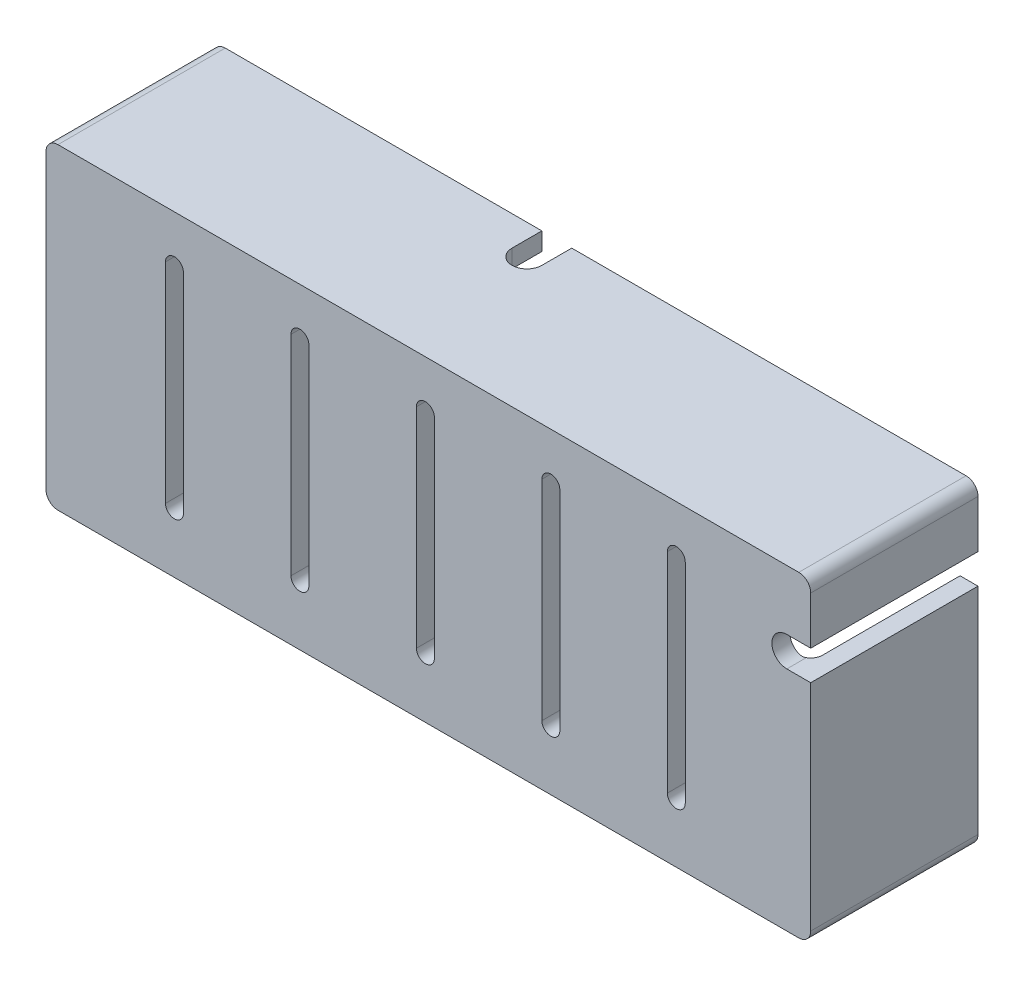
SolidWorks part; units mm, degrees
ref_plane "Plan de face" through (0, 0, 0) normal (0, 0, 1) x (1, 0, 0)
ref_plane "Plan de dessus" through (0, 0, 0) normal (0, 1, 0) x (1, 0, 0)
ref_plane "Plan de droite" through (0, 0, 0) normal (1, 0, 0) x (0, 0, -1)
sketch "Esquisse1" plane through (0, 0, 0) normal (0, 0, 1) x (1, 0, 0)
  line L0 (-61, 23.5) -> (61, -23.5) construction
  line L1 (-61, 23.5) -> (61, 23.5)
  line L2 (-61, 23.5) -> (-61, -23.5)
  line L3 (-61, -23.5) -> (61, -23.5)
  line L4 (61, 23.5) -> (61, -23.5)
  line L5 (-64, -26.5) -> (64, 26.5) construction
  line L6 (-64, 26.5) -> (64, 26.5)
  line L7 (-64, 26.5) -> (-64, -26.5)
  line L8 (-64, -26.5) -> (64, -26.5)
  line L9 (64, 26.5) -> (64, -26.5)
  dimension "D1" = 122
  dimension "D2" = 47
  dimension "D3" = 3
  dimension "D4" = 3
extrude "Boss.-Extru.1" add sketch "Esquisse1" along normal blind 25
sketch "Esquisse2" plane through (0, 0, 25) normal (0, 0, 1) x (1, 0, 0)
  line L1 (-64, 26.5) -> (64, 26.5)
  line L2 (-64, 26.5) -> (-64, -26.5)
  line L3 (-64, -26.5) -> (64, -26.5)
  line L4 (64, 26.5) -> (64, -26.5)
extrude "Boss.-Extru.2" add sketch "Esquisse2" along normal blind 3
sketch "Esquisse3" plane through (0, 0, 25) normal (0, 0, -1) x (-1, 0, 0)
  line L0 (-61, 18.5) -> (-56, 23.5)
  line L1 (-61, -23.5) -> (-61, 23.5) construction
  line L2 (-61, 23.5) -> (61, 23.5) construction
  line L3 (-56, 23.5) -> (-61, 23.5)
  line L4 (-61, 23.5) -> (-61, 18.5)
  line L5 (-61, 18.5) -> (-61.0063, 18.5)
  line L7 (-61, -23.5) -> (-61, -18.5)
  line L8 (-61, -18.5) -> (-56, -23.5)
  line L9 (61, -23.5) -> (-61, -23.5) construction
  line L10 (-56, -23.5) -> (-61, -23.5)
  line L11 (61, 23.5) -> (56, 23.5)
  line L12 (-61, 23.5) -> (61, 23.5) construction
  line L13 (56, 23.5) -> (61, 18.5)
  line L14 (61, 23.5) -> (61, -23.5) construction
  line L15 (61, 18.5) -> (61, 23.5)
  line L16 (61, -23.5) -> (61, -18.5)
  line L17 (61, 23.5) -> (61, -23.5) construction
  line L18 (61, -18.5) -> (56, -23.5)
  line L19 (61, -23.5) -> (-61, -23.5) construction
  line L20 (56, -23.5) -> (61, -23.5)
  line M1 (61, -23.5) -> (61, 23.5)
  line M2 (61, 23.5) -> (-61, 23.5)
  dimension "D1" = 5
  dimension "D2" = 5
  dimension "D3" = 5
  dimension "D4" = 5
  dimension "D5" = 5
  dimension "D6" = 5
  dimension "D7" = 5
  dimension "D8" = 5
extrude "Boss.-Extru.3" add sketch "Esquisse3" along normal blind 25 contours L13 M2 M1 | L16 L18 L20 | L7 L8 L10 | L0 L3 L4
sketch "Esquisse4" plane through (0, 0, 28) normal (0, 0, 1) x (1, 0, 0)
  line L1 (-64, 0) -> (64, 0) construction
  line L2 (-44, 18.5) -> (-44, -16.5)
  line L3 (-23, 18.5) -> (-23, -16.5)
  line L4 (-41, 18.5) -> (-41, -16.5)
  line L6 (-64, 26.5) -> (-64, -26.5) construction
  line L7 (-20, 18.5) -> (-20, -16.5)
  line L8 (-2, 18.5) -> (-2, -16.5)
  line L9 (1, 18.5) -> (1, -16.5)
  line L10 (19, 18.5) -> (19, -16.5)
  line L11 (22, 18.5) -> (22, -16.5)
  line L12 (40, 18.5) -> (40, -16.5)
  line L13 (43, 18.5) -> (43, -16.5)
  arc A0 (-44, 18.5) -> (-41, 18.5) centre (-42.5, 18.5) cw
  arc A1 (-44, -16.5) -> (-41, -16.5) centre (-42.5, -16.5) ccw
  arc A2 (-23, -16.5) -> (-20, -16.5) centre (-21.5, -16.5) ccw
  arc A3 (-23, 18.5) -> (-20, 18.5) centre (-21.5, 18.5) cw
  arc A4 (-2, -16.5) -> (1, -16.5) centre (-0.5, -16.5) ccw
  arc A5 (-2, 18.5) -> (1, 18.5) centre (-0.5, 18.5) cw
  arc A6 (19, -16.5) -> (22, -16.5) centre (20.5, -16.5) ccw
  arc A7 (19, 18.5) -> (22, 18.5) centre (20.5, 18.5) cw
  arc A8 (40, -16.5) -> (43, -16.5) centre (41.5, -16.5) ccw
  arc A9 (40, 18.5) -> (43, 18.5) centre (41.5, 18.5) cw
  dimension "D1" = 35
  dimension "D2" = 18.5
  dimension "D3" = 3
  dimension "D4" = 20
  dimension "D5" = 5
extrude "Enlèv. mat.-Extru.1" cut sketch "Esquisse4" against normal blind 3
sketch "Esquisse5" plane through (0, 0, 0) normal (0, 0, -1) x (-1, 0, 0)
  line L0 (56, 23.5) -> (61, 18.5) construction
  line L1 (-64, 26.5) -> (-55.783, 18.283) construction
  line L2 (-64, -26.5) -> (-55.3868, -17.8868) construction
  line L3 (-61, -18.5) -> (-56, -23.5) construction
  line L4 (64, -26.5) -> (56.4817, -18.9817) construction
  line L5 (61, -18.5) -> (56, -23.5) construction
  line L6 (61, -18.5) -> (56, -23.5) construction
  line L7 (64, 26.5) -> (55.3834, 17.8834) construction
  line L8 (56, 23.5) -> (61, 18.5) construction
  line L9 (-61, 18.5) -> (-56, 23.5) construction
  circle A0 centre (-60.6213, 23.1213) radius 1
  circle A1 centre (60.6213, 23.1213) radius 1
  circle A2 centre (-60.6213, -23.1213) radius 1
  circle A3 centre (60.6213, -23.1213) radius 1
  dimension "D1" = 2
  dimension "D2" = 2
  dimension "D3" = 2
  dimension "D4" = 2
  dimension "D5" = 3
  dimension "D6" = 3
  dimension "D7" = 3
  dimension "D8" = 3
extrude "Enlèv. mat.-Extru.2" cut sketch "Esquisse5" against normal blind 20
fillet "Congé1" radius 5 1 edges at (56, 23.5, 12.5)
fillet "Congé2" radius 5 7 edges at (-61, -18.5, 12.5) (-56, -23.5, 12.5) (-61, 18.5, 12.5) (-56, 23.5, 12.5) (56, -23.5, 12.5) (61, -18.5, 12.5) (61, 18.5, 12.5)
sketch "Esquisse6" plane through (64, 0, 0) normal (1, 0, 0) x (0, 0, -1)
  line L0 (-28, -26.5) -> (-28, 26.5) construction
  line L1 (-28, 16.5) -> (0, 16.5)
  line L2 (-28, 16.5) -> (-28, 11.5)
  line L3 (-28, 11.5) -> (0, 11.5)
  line L4 (0, 16.5) -> (0, 11.5)
  line L5 (0, -26.5) -> (0, 26.5) construction
  line L6 (-28, 26.5) -> (0, 26.5) construction
  dimension "D1" = 5
  dimension "D2" = 10
extrude "Enlèv. mat.-Extru.3" cut sketch "Esquisse6" against normal blind 3
sketch "Esquisse7" plane through (0, 26.5, 0) normal (0, 1, 0) x (1, 0, 0)
  line L0 (64, 0) -> (-64, 0) construction
  line L1 (-9, 0) -> (-4, 0)
  line L2 (-9, 0) -> (-9, -5)
  line L3 (-64, 0) -> (64, 0) construction
  line L4 (-4, 0) -> (-4, -5)
  line L5 (-64, -28) -> (-64, 0) construction
  arc A0 (-9, -5) -> (-4, -5) centre (-6.5, -5) ccw
  dimension "D4" = 2.5
  dimension "D1" = 5
  dimension "D2" = 5
  dimension "D3" = 55
extrude "Enlèv. mat.-Extru.4" cut sketch "Esquisse7" against normal blind 8
sketch "Esquisse9" plane through (0, -26.5, 0) normal (0, -1, 0) x (1, 0, 0)
  line L0 (-29, 0) -> (64, 0) construction
  line L1 (44, 0) -> (49, 0)
  line L2 (44, 0) -> (44, 5)
  line L4 (49, 0) -> (49, 5)
  line L5 (64, 28) -> (64, 0) construction
  arc A0 (44, 5) -> (49, 5) centre (46.5, 5) cw
  dimension "D3" = 2.5
  dimension "D1" = 5
  dimension "D2" = 15
  dimension "D4" = 5
extrude "Enlèv. mat.-Extru.6" cut sketch "Esquisse9" against normal blind 8
sketch "Esquisse10" plane through (0, 0, 28) normal (0, 0, 1) x (1, 0, 0)
  line L1 (61, 16.5) -> (60, 16.5)
  line L2 (61, 16.5) -> (61, 11.5)
  line L3 (61, 11.5) -> (60, 11.5)
  arc A0 (60, 16.5) -> (60, 11.5) centre (60, 14) ccw
  dimension "D1" = 2.5
  dimension "D2" = 1
  dimension "D3" = 5
extrude "Enlèv. mat.-Extru.7" cut sketch "Esquisse10" against normal blind 8
sketch "Esquisse13" plane through (-64, 0, 0) normal (-1, 0, 0) x (0, 0, 1)
  line L0 (0, 26.5) -> (0, -26.5) construction
  line L1 (0, 3) -> (2, 3)
  line L2 (0, 3) -> (0, -3)
  line L3 (0, -3) -> (2, -3)
  line L4 (2, 3) -> (2, -3)
  line L5 (0, 0) -> (2, 0) construction
  dimension "D1" = 2
  dimension "D2" = 6
extrude "Enlèv. mat.-Extru.8" cut sketch "Esquisse13" against normal blind 3
fillet "Congé4" radius 2 16 edges at (60.6057, 18.3751, 25) (58.5, 21, 25) (55.8423, 23.1194, 25) (61, -2.4645, 25) (60.6194, -18.3423, 25) (58.5, -21, 25) (55.8423, -23.1194, 25) (0, -23.5, 25) (-55.8423, -23.1194, 25) (-58.5, -21, 25) (-60.6194, -18.3423, 25) (-61, 0, 25) (-60.6194, 18.3423, 25) (-58.5, 21, 25) (-55.8423, 23.1194, 25) (0, 23.5, 25)
fillet "Congé5" radius 2 4 edges at (-64, 26.5, 14) (64, 26.5, 14) (64, -26.5, 14) (-64, -26.5, 14)
